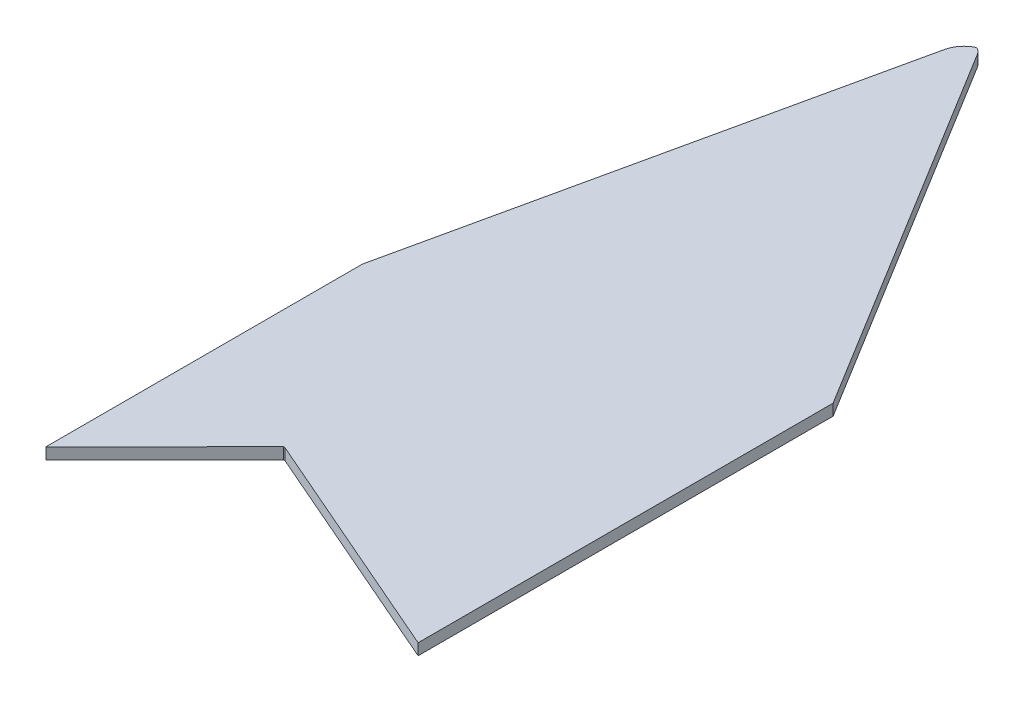
SolidWorks part; units mm, degrees
ref_plane "Front Plane" through (0, 0, 0) normal (0, 0, 1) x (1, 0, 0)
ref_plane "Top Plane" through (0, 0, 0) normal (0, 1, 0) x (1, 0, 0)
ref_plane "Right Plane" through (0, 0, 0) normal (1, 0, 0) x (0, 0, -1)
sketch "Sketch2" plane through (0, 0, 0) normal (0, 1, 0) x (1, 0, 0)
  line L0 (-2.5437, -35.2007) -> (-15.8873, -48.5467)
  line L1 (-15.8873, -48.5467) -> (-15.8873, -12.9752)
  line L2 (-15.8873, -12.9752) -> (-4.0644, 40.6244)
  line L3 (-2.362, -35.2007) -> (24.1127, -46.7093)
  line L4 (24.1127, -46.7093) -> (24.1127, -0.0538)
  line L5 (24.1127, -0.0538) -> (-1.7715, 42.0691)
  line L6 (-2.5437, -35.2007) -> (-2.362, -35.2007)
  line L7 (-1.7769, 41.7993) -> (-1.7906, 41.7993)
  arc A8 (-4.0644, 40.6244) -> (-2.4529, 42.6404) centre (-1.21, 39.9947) cw
  arc A9 (-1.7715, 42.0691) -> (-2.4529, 42.6404) centre (-2.9683, 41.3336) ccw
  point P13 (-2.4529, -35.2007)
  dimension "D2" = 0
  dimension "D1" = 40
extrude "Boss-Extrude1" add sketch "Sketch2" along normal blind 1.27
